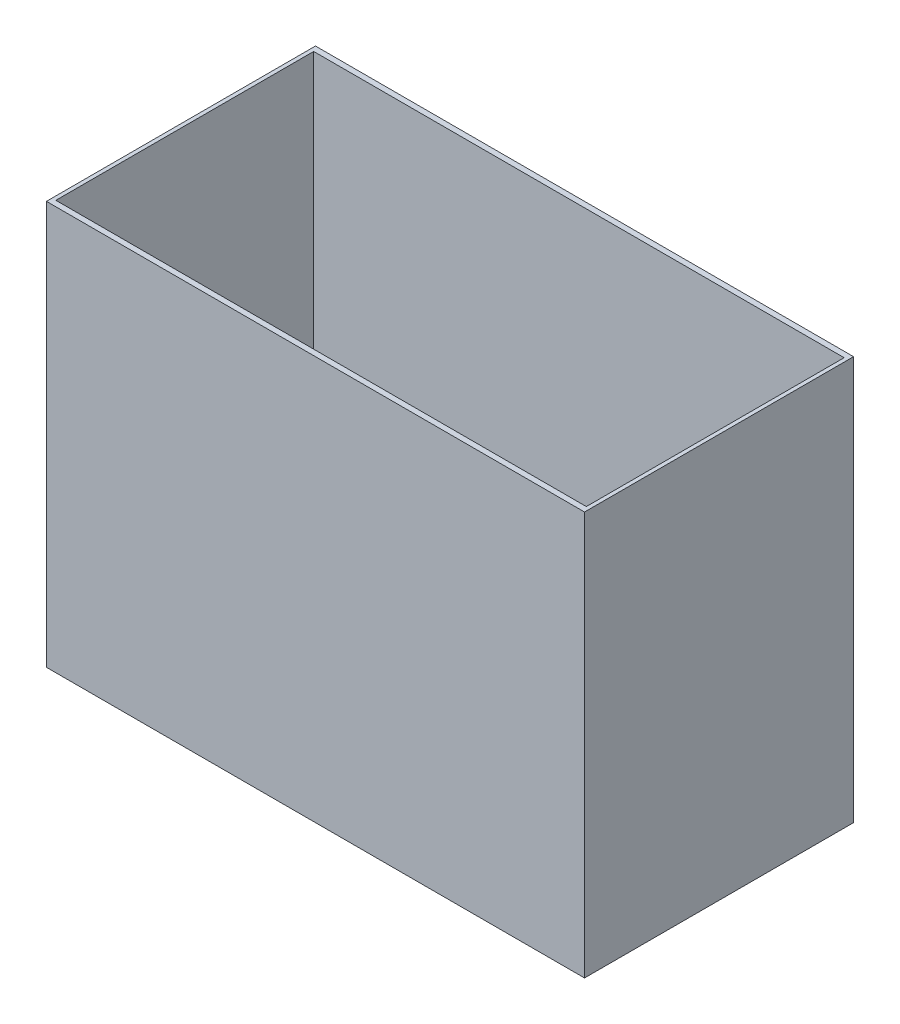
SolidWorks part; units mm, degrees
ref_plane "Front Plane" through (0, 0, 0) normal (0, 0, 1) x (1, 0, 0)
ref_plane "Top Plane" through (0, 0, 0) normal (0, 1, 0) x (1, 0, 0)
ref_plane "Right Plane" through (0, 0, 0) normal (1, 0, 0) x (0, 0, -1)
other "Bounding Box"
ref_plane "Default Plane" through (-292.1, 0, -139.7) normal (0, 1, 0) x (1, 0, 0)
sketch "Sketch1" plane through (0, 0, 0) normal (0, 1, 0) x (1, 0, 0)
  line L0 (-292.1, 0) -> (292.1, 0) construction
  line L1 (-292.1, 139.7) -> (292.1, 139.7)
  line L2 (-292.1, 139.7) -> (-292.1, -139.7)
  line L3 (-292.1, -139.7) -> (292.1, -139.7)
  line L4 (292.1, 139.7) -> (292.1, -139.7)
  line L5 (0, 139.7) -> (0, -139.7) construction
  point P8 (0, 0)
  dimension "D1" = 584.2
  dimension "D2" = 279.4
extrude "Boss-Extrude1" add sketch "Sketch1" along normal blind 12.7
sketch "Sketch2" plane through (0, 12.7, 0) normal (0, 1, 0) x (1, 0, 0)
  line L0 (-245.9259, -63.5) -> (-55.3589, -63.5) construction
  line L1 (-241.3, -120.6497) -> (-152.4, -120.6497)
  line L2 (-241.3, -120.6497) -> (-241.3, -101.5997)
  line L3 (-241.3, -101.5997) -> (-152.4, -101.5997)
  line L4 (-152.4, -120.6497) -> (-152.4, -101.5997)
  line L5 (-241.3, -120.6497) -> (-152.4, -101.5997) construction
  line L6 (-241.3, -101.5997) -> (-152.4, -120.6497) construction
  line L7 (-292.1, 139.7) -> (-292.1, -139.7) construction
  line L8 (-292.1, 0) -> (292.1, 0) construction
  line L9 (292.1, -139.7) -> (292.1, 139.7) construction
  line L10 (0, 0) -> (0, 121.6784) construction
  line L11 (241.3, -101.5997) -> (152.4, -120.6497) construction
  line L12 (241.3, -120.6497) -> (152.4, -101.5997) construction
  line L13 (152.4, -120.6497) -> (152.4, -101.5997)
  line L14 (241.3, -101.5997) -> (152.4, -101.5997)
  line L15 (241.3, -120.6497) -> (241.3, -101.5997)
  line L16 (241.3, -120.6497) -> (152.4, -120.6497)
  point P0 (-196.85, -111.1247)
  point P17 (196.85, -111.1247)
  dimension "D1" = 19.05
  dimension "D2" = 88.9
  dimension "D3" = 38.0997
  dimension "D4" = 50.8
  dimension "D5" = 63.5
extrude "Boss-Extrude2" [suppressed] add sketch "Sketch2" along normal blind 304.8 separate body contours L2 L1 L4 L3
pattern_linear "LPattern1" [suppressed] count 2 spacing 304.8
pattern_linear "LPattern2" [suppressed] count 2 spacing 215.9
sketch "Sketch3" plane through (0, 0, 0) normal (0, 1, 0) x (1, 0, 0)
  line L1 (-304.8, -152.4) -> (304.8, -152.4)
  line L2 (-304.8, -152.4) -> (-304.8, 152.4)
  line L3 (-304.8, 152.4) -> (304.8, 152.4)
  line L4 (304.8, -152.4) -> (304.8, 152.4)
  line L5 (-304.8, -152.4) -> (304.8, 152.4) construction
  line L6 (-304.8, 152.4) -> (304.8, -152.4) construction
  line L7 (-300.482, -146.05) -> (300.482, -146.05)
  line L8 (-300.482, -146.05) -> (-300.482, 146.05)
  line L9 (-300.482, 146.05) -> (300.482, 146.05)
  line L10 (300.482, -146.05) -> (300.482, 146.05)
  line L11 (-300.482, -146.05) -> (300.482, 146.05) construction
  line L12 (-300.482, 146.05) -> (300.482, -146.05) construction
  point P0 (0, 0)
  point P6 (0, 0)
  dimension "D1" = 609.6
  dimension "D2" = 304.8
  dimension "D3" = 292.1
  dimension "D4" = 600.964
extrude "Boss-Extrude3" add sketch "Sketch3" along normal blind 457.2 separate body
sketch "Sketch4" plane through (0, 12.7, 0) normal (0, 1, 0) x (1, 0, 0)
  line L0 (292.1, 139.7) -> (-292.1, 139.7) construction
  line L1 (292.1, -139.7) -> (292.1, 139.7) construction
  circle A0 centre (254, 101.6) radius 2.7781
  dimension "D1" = 5.5562
  dimension "D2" = 38.1
  dimension "D3" = 38.1
extrude "Cut-Extrude1" cut sketch "Sketch4" against normal through all
mirror "Mirror1" about plane through (0, 0, 0) normal (0, 0, 1) of "Cut-Extrude1"
